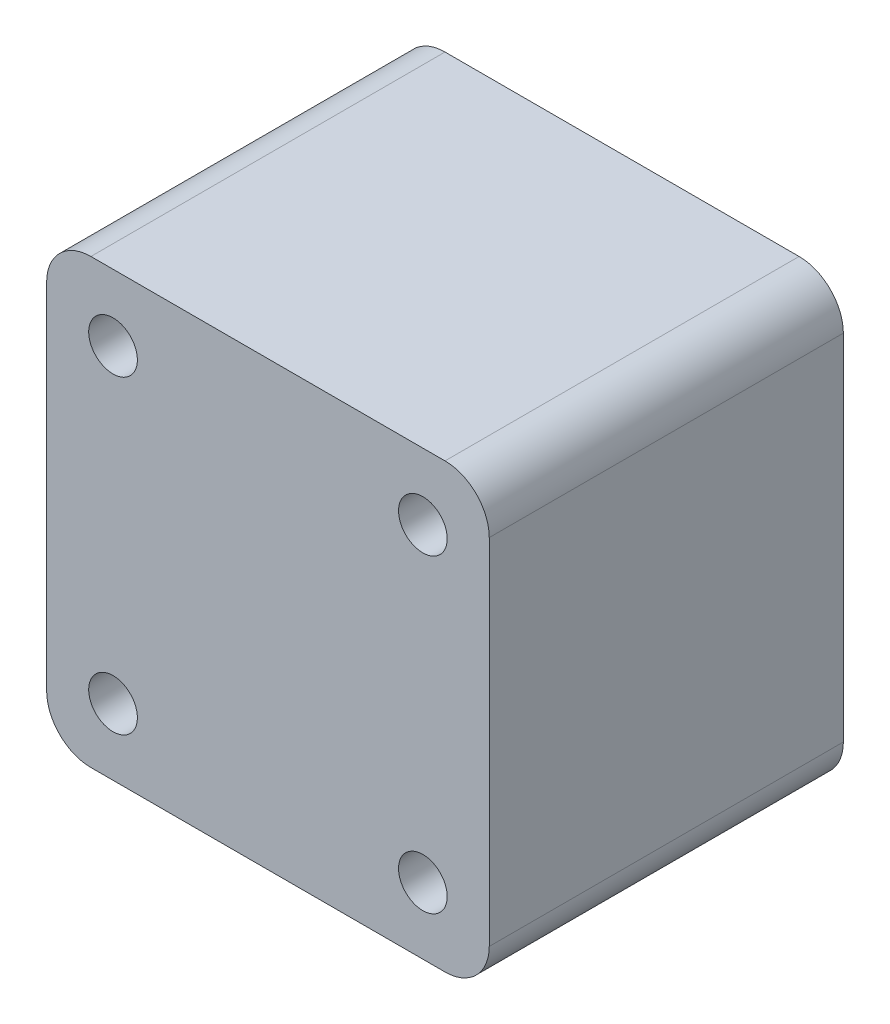
SolidWorks part; units mm, degrees
ref_plane "Front" through (0, 0, 0) normal (0, 0, 1) x (1, 0, 0)
ref_plane "Top" through (0, 0, 0) normal (0, 1, 0) x (1, 0, 0)
ref_plane "Right" through (0, 0, 0) normal (1, 0, 0) x (0, 0, -1)
sketch "草图1" plane through (0, 0, 0) normal (0, 0, 1) x (1, 0, 0)
  line L1 (-50, 50) -> (50, 50)
  line L2 (-50, 50) -> (-50, -50)
  line L3 (-50, -50) -> (50, -50)
  line L4 (50, 50) -> (50, -50)
  line L5 (-50, 50) -> (50, -50) construction
  line L6 (-50, -50) -> (50, 50) construction
  point P0 (0, 0)
extrude "凸台-拉伸1" add sketch "草图1" along normal blind 80
sketch "草图2" plane through (0, 0, 80) normal (0, 0, 1) x (1, 0, 0)
  line L0 (-50, 50) -> (-50, -50) construction
  line L1 (50, 50) -> (-50, 50) construction
  line L2 (-50, -50) -> (50, -50) construction
  line L3 (50, -50) -> (50, 50) construction
  circle A0 centre (-35, 35) radius 5.5
  circle A1 centre (35, 35) radius 5.5
  circle A2 centre (-35, -35) radius 5.5
  circle A3 centre (35, -35) radius 5.5
  dimension "D1" = 15
  dimension "D2" = 15
  dimension "D4" = 15
  dimension "D3" = 15
extrude "切除-拉伸2" cut sketch "草图2" against normal through all
fillet "圆角1" radius 10 1 edges at (-50, 50, 40)
fillet "圆角2" radius 10 3 edges at (50, 50, 40) (50, -50, 40) (-50, -50, 40)
